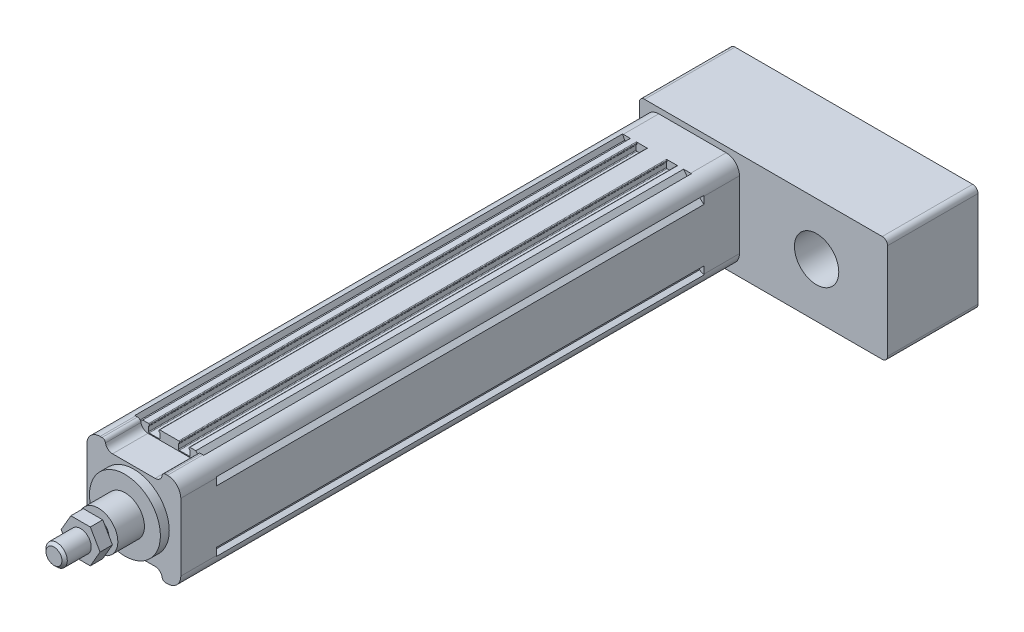
SolidWorks part; units mm, degrees
ref_plane "Front" through (0, 0, 0) normal (0, 0, 1) x (1, 0, 0)
ref_plane "Top" through (0, 0, 0) normal (0, 1, 0) x (1, 0, 0)
ref_plane "Right" through (0, 0, 0) normal (1, 0, 0) x (0, 0, -1)
sketch "草图1" plane through (0, 0, 0) normal (0, 0, 1) x (1, 0, 0)
  line L0 (19.7737, 3) -> (23.3, 3)
  line L1 (23.3, 3) -> (23.3, -3)
  line L2 (23.3, -3) -> (19.7737, -3)
  line L3 (-19.7737, -3) -> (-23.3, -3)
  line L4 (-23.3, -3) -> (-23.3, 3)
  line L5 (-23.3, 3) -> (-19.7737, 3)
  line L6 (-18.2, 24) -> (-19.4434, 26.4869)
  line L7 (-26.4869, 19.4434) -> (-24, 18.2)
  line L8 (-24, 18.2) -> (-24, 17.1)
  line L9 (-24, 17.1) -> (-26.5, 15)
  line L10 (-26.5, 15) -> (-26.5, -15)
  line L11 (-26.5, -15) -> (-24, -17.1)
  line L12 (-24, -17.1) -> (-24, -18.2)
  line L13 (-24, -18.2) -> (-26.4869, -19.4434)
  line L14 (-19.4434, -26.4869) -> (-18.2, -24)
  line L15 (-18.2, -24) -> (-17.1, -24)
  line L16 (-17.1, -24) -> (-15, -26.5)
  line L17 (-15, -26.5) -> (-11.65, -26.5)
  line L18 (-11.25, -26.1) -> (-11.25, -25.6)
  line L19 (-11.65, -25.2) -> (-11.75, -25.2)
  line L20 (-11.75, -25.2) -> (-11.75, -22.4)
  line L21 (-11.35, -22) -> (-5.65, -22)
  line L22 (-5.25, -22.4) -> (-5.25, -25.2)
  line L23 (-5.25, -25.2) -> (-5.35, -25.2)
  line L24 (-5.75, -25.6) -> (-5.75, -26.1)
  line L25 (-5.35, -26.5) -> (5.35, -26.5)
  line L26 (5.75, -26.1) -> (5.75, -25.6)
  line L27 (5.35, -25.2) -> (5.25, -25.2)
  line L28 (5.25, -25.2) -> (5.25, -22.4)
  line L29 (5.65, -22) -> (11.35, -22)
  line L30 (11.75, -22.4) -> (11.75, -25.2)
  line L31 (11.75, -25.2) -> (11.65, -25.2)
  line L32 (11.25, -25.6) -> (11.25, -26.1)
  line L33 (11.65, -26.5) -> (15, -26.5)
  line L34 (15, -26.5) -> (17.1, -24)
  line L35 (17.1, -24) -> (18.2, -24)
  line L36 (18.2, -24) -> (19.4434, -26.4869)
  line L37 (26.4869, -19.4434) -> (24, -18.2)
  line L38 (24, -18.2) -> (24, -17.1)
  line L39 (24, -17.1) -> (26.5, -15)
  line L40 (26.5, -15) -> (26.5, 15)
  line L41 (26.5, 15) -> (24, 17.1)
  line L42 (24, 17.1) -> (24, 18.2)
  line L43 (24, 18.2) -> (26.4869, 19.4434)
  line L44 (19.4434, 26.4869) -> (18.2, 24)
  line L45 (18.2, 24) -> (17.1, 24)
  line L46 (17.1, 24) -> (15, 26.5)
  line L47 (15, 26.5) -> (11.65, 26.5)
  line L48 (11.25, 26.1) -> (11.25, 25.6)
  line L49 (11.65, 25.2) -> (11.75, 25.2)
  line L50 (11.75, 25.2) -> (11.75, 22.4)
  line L51 (11.35, 22) -> (5.65, 22)
  line L52 (5.25, 22.4) -> (5.25, 25.2)
  line L53 (5.25, 25.2) -> (5.35, 25.2)
  line L54 (5.75, 25.6) -> (5.75, 26.1)
  line L55 (5.35, 26.5) -> (-5.35, 26.5)
  line L56 (-5.75, 26.1) -> (-5.75, 25.6)
  line L57 (-5.35, 25.2) -> (-5.25, 25.2)
  line L58 (-5.25, 25.2) -> (-5.25, 22.4)
  line L59 (-5.65, 22) -> (-11.35, 22)
  line L60 (-11.75, 22.4) -> (-11.75, 25.2)
  line L61 (-11.75, 25.2) -> (-11.65, 25.2)
  line L62 (-11.25, 25.6) -> (-11.25, 26.1)
  line L63 (-11.65, 26.5) -> (-15, 26.5)
  line L64 (-15, 26.5) -> (-17.1, 24)
  line L65 (-17.1, 24) -> (-18.2, 24)
  arc A0 (19.7737, 3) -> (-19.7737, 3) centre (0, 0) ccw
  arc A1 (-19.7737, -3) -> (19.7737, -3) centre (0, 0) ccw
  circle A2 centre (19, 19) radius 2.1
  circle A3 centre (19, -19) radius 2.1
  circle A4 centre (-19, -19) radius 2.1
  circle A5 centre (-19, 19) radius 2.1
  arc A6 (-19.4434, 26.4869) -> (-26.4869, 19.4434) centre (-19, 19) ccw
  arc A7 (-26.4869, -19.4434) -> (-19.4434, -26.4869) centre (-19, -19) ccw
  arc A8 (-11.65, -26.5) -> (-11.25, -26.1) centre (-11.65, -26.1) ccw
  arc A9 (-11.25, -25.6) -> (-11.65, -25.2) centre (-11.65, -25.6) ccw
  arc A10 (-11.35, -22) -> (-11.75, -22.4) centre (-11.35, -22.4) ccw
  arc A11 (-5.25, -22.4) -> (-5.65, -22) centre (-5.65, -22.4) ccw
  arc A12 (-5.35, -25.2) -> (-5.75, -25.6) centre (-5.35, -25.6) ccw
  arc A13 (-5.75, -26.1) -> (-5.35, -26.5) centre (-5.35, -26.1) ccw
  arc A14 (5.35, -26.5) -> (5.75, -26.1) centre (5.35, -26.1) ccw
  arc A15 (5.75, -25.6) -> (5.35, -25.2) centre (5.35, -25.6) ccw
  arc A16 (5.65, -22) -> (5.25, -22.4) centre (5.65, -22.4) ccw
  arc A17 (11.75, -22.4) -> (11.35, -22) centre (11.35, -22.4) ccw
  arc A18 (11.65, -25.2) -> (11.25, -25.6) centre (11.65, -25.6) ccw
  arc A19 (11.25, -26.1) -> (11.65, -26.5) centre (11.65, -26.1) ccw
  arc A20 (19.4434, -26.4869) -> (26.4869, -19.4434) centre (19, -19) ccw
  arc A21 (26.4869, 19.4434) -> (19.4434, 26.4869) centre (19, 19) ccw
  arc A22 (11.65, 26.5) -> (11.25, 26.1) centre (11.65, 26.1) ccw
  arc A23 (11.25, 25.6) -> (11.65, 25.2) centre (11.65, 25.6) ccw
  arc A24 (11.35, 22) -> (11.75, 22.4) centre (11.35, 22.4) ccw
  arc A25 (5.25, 22.4) -> (5.65, 22) centre (5.65, 22.4) ccw
  arc A26 (5.35, 25.2) -> (5.75, 25.6) centre (5.35, 25.6) ccw
  arc A27 (5.75, 26.1) -> (5.35, 26.5) centre (5.35, 26.1) ccw
  arc A28 (-5.35, 26.5) -> (-5.75, 26.1) centre (-5.35, 26.1) ccw
  arc A29 (-5.75, 25.6) -> (-5.35, 25.2) centre (-5.35, 25.6) ccw
  arc A30 (-5.65, 22) -> (-5.25, 22.4) centre (-5.65, 22.4) ccw
  arc A31 (-11.75, 22.4) -> (-11.35, 22) centre (-11.35, 22.4) ccw
  arc A32 (-11.65, 25.2) -> (-11.25, 25.6) centre (-11.65, 25.6) ccw
  arc A33 (-11.25, 26.1) -> (-11.65, 26.5) centre (-11.65, 26.1) ccw
extrude "凸台-拉伸1" add sketch "草图1" along normal blind 275
sketch "草图6" plane through (0, 0, 275) normal (0, 0, 1) x (1, 0, 0)
  line L0 (0, 0) -> (19, 0) construction
  line L2 (-26.5, -19) -> (-26.5, 19)
  line L3 (-19, 26.5) -> (-17.9161, 26.5)
  line L4 (26.5, -19) -> (26.5, 19)
  line L5 (-26.5, -26.5) -> (26.5, 26.5) construction
  line L6 (-26.5, 26.5) -> (26.5, -26.5) construction
  line L7 (-12, 21.5) -> (12, 21.5)
  line L9 (19, 26.5) -> (17.9161, 26.5)
  line L10 (19, -26.5) -> (17.9161, -26.5)
  line L11 (-12, -21.5) -> (12, -21.5)
  line L12 (-19, -26.5) -> (-17.9161, -26.5)
  arc A0 (12, 21.5) -> (15.9441, 24.8333) centre (12, 25.5) ccw
  arc A1 (-15.9441, 24.8333) -> (-12, 21.5) centre (-12, 25.5) ccw
  arc A2 (-15.9441, 24.8333) -> (-17.9161, 26.5) centre (-17.9161, 24.5) ccw
  arc A3 (15.9441, 24.8333) -> (17.9161, 26.5) centre (17.9161, 24.5) cw
  arc A4 (-26.5, -19) -> (-19, -26.5) centre (-19, -19) ccw
  arc A5 (19, -26.5) -> (26.5, -19) centre (19, -19) ccw
  arc A6 (26.5, 19) -> (19, 26.5) centre (19, 19) ccw
  arc A7 (-26.5, 19) -> (-19, 26.5) centre (-19, 19) cw
  arc A8 (15.9441, -24.8333) -> (17.9161, -26.5) centre (17.9161, -24.5) ccw
  arc A9 (12, -21.5) -> (15.9441, -24.8333) centre (12, -25.5) cw
  arc A10 (-15.9441, -24.8333) -> (-12, -21.5) centre (-12, -25.5) cw
  arc A11 (-15.9441, -24.8333) -> (-17.9161, -26.5) centre (-17.9161, -24.5) cw
  point P0 (0, 0)
  point P9 (0, 21.5)
  point P13 (20, 20.8461)
  point P16 (-12, 20.8461)
  dimension "D5" = 4
  dimension "D6" = 2
  dimension "D7" = 2
  dimension "D9" = 7.5
  dimension "D1" = 53
  dimension "D2" = 53
  dimension "D3" = 26.5
  dimension "D4" = 24
  dimension "D8" = 5
extrude "凸台-拉伸2" add sketch "草图6" along normal blind 20
sketch "草图7" plane through (0, 0, 295) normal (0, 0, 1) x (1, 0, 0)
  circle A0 centre (0, 0) radius 20
  dimension "D1" = 40
extrude "凸台-拉伸3" add sketch "草图7" along normal blind 5
sketch "草图9" plane through (0, 0, 300) normal (0, 0, 1) x (1, 0, 0)
  circle A0 centre (0, 0) radius 11
  dimension "D1" = 22
extrude "凸台-拉伸4" add sketch "草图9" along normal blind 15
sketch "草图10" plane through (0, 0, 315) normal (0, 0, 1) x (1, 0, 0)
  circle A0 centre (0, 0) radius 6
  dimension "D1" = 12
extrude "凸台-拉伸5" add sketch "草图10" along normal blind 25
sketch "草图11" plane through (0, 0, 0) normal (0, 0, -1) x (-1, 0, 0)
  line L1 (-19, -26.5) -> (19, -26.5)
  line L2 (-26.5, -19) -> (-26.5, 19)
  line L3 (-19, 26.5) -> (19, 26.5)
  line L4 (26.5, -19) -> (26.5, 19)
  line L5 (-26.5, -26.5) -> (26.5, 26.5) construction
  line L6 (-26.5, 26.5) -> (26.5, -26.5) construction
  arc A0 (-26.5, -19) -> (-19, -26.5) centre (-19, -19) ccw
  arc A1 (19, -26.5) -> (26.5, -19) centre (19, -19) ccw
  arc A2 (26.5, 19) -> (19, 26.5) centre (19, 19) ccw
  arc A3 (-26.5, 19) -> (-19, 26.5) centre (-19, 19) cw
  point P0 (0, 0)
  dimension "D3" = 7.5
  dimension "D1" = 53
  dimension "D2" = 53
extrude "凸台-拉伸6" add sketch "草图11" along normal blind 20
sketch "草图12" plane through (0, 0, -20) normal (0, 0, -1) x (-1, 0, 0)
  line L1 (-107, -30.4042) -> (27, -30.4042)
  line L2 (-110, -27.4042) -> (-110, 26.5958)
  line L3 (-107, 29.5958) -> (27, 29.5958)
  line L4 (30, -27.4042) -> (30, 26.5958)
  line L5 (-110, -30.4042) -> (30, 29.5958) construction
  line L6 (-110, 29.5958) -> (30, -30.4042) construction
  arc A0 (27, 29.5958) -> (30, 26.5958) centre (27, 26.5958) cw
  arc A1 (30, -27.4042) -> (27, -30.4042) centre (27, -27.4042) cw
  arc A2 (-110, -27.4042) -> (-107, -30.4042) centre (-107, -27.4042) ccw
  arc A3 (-110, 26.5958) -> (-107, 29.5958) centre (-107, 26.5958) cw
  point P0 (-40, -0.4042)
  dimension "D4" = 3
  dimension "D1" = 60
  dimension "D2" = 140
  dimension "D3" = 30
extrude "凸台-拉伸7" add sketch "草图12" along normal blind 51
sketch "草图13" plane through (0, 0, -20) normal (0, 0, 1) x (1, 0, 0)
  circle A0 centre (70, 0) radius 12.5
  dimension "D2" = 25
  dimension "D1" = 70
extrude "切除-拉伸2" cut sketch "草图13" against normal blind 30
hole_wizard "M6 螺纹孔1" positions "草图14" profile "草图15" tap size "M6" standard "GB"
sketch "草图14" plane through (0, 0, -71) normal (0, 0, -1) x (-1, 0, 0)
  line L0 (30, -27.4042) -> (30, 26.5958) construction
  point P0 (19, -19)
  dimension "D1" = 11
  dimension "D2" = 19
sketch "草图15" plane through (-19, -19, -71) normal (1, 0, 0) x (0, 1, 0)
  line L0 (0, 0) -> (0, 16.5022)
  line L1 (0, 16.5022) -> (2.5, 15)
  line L2 (2.5, 15) -> (2.5, 0)
  line L5 (2.5, 0) -> (0, 0)
  line L10 (0, 16.5022) -> (-2.5, 15) construction
  line L11 (0, -6.35) -> (0, 107.95) construction
  dimension "螺纹孔钻头直径" = 5
  dimension "螺纹孔钻头深度" = 15
  dimension "导头角度" = 118
cosmetic thread "孔螺蚊线4" parameters "D1"=12, "D2"=6
pattern_linear "阵列(线性)1" count 2 spacing 38 along (0, 1, 0) count 2 spacing 38 along (1, 0, 0) of "M6 螺纹孔1"
hole_wizard "M6 螺纹孔2" positions "草图16" profile "草图17" tap size "M6" standard "GB"
sketch "草图16" plane through (0, 0, -71) normal (0, 0, -1) x (-1, 0, 0)
  circle A1 centre (-19, 19) radius 2.5 construction
  circle A2 centre (-19, -19) radius 2.5 construction
  point P0 (-84, -19)
  point P2 (-84, 19)
  dimension "D3" = 65
  dimension "D1" = 19
  dimension "D2" = 19
  dimension "D4" = 65
sketch "草图17" plane through (84, -19, -71) normal (1, 0, 0) x (0, 1, 0)
  line L0 (0, 0) -> (0, 16.5022)
  line L1 (0, 16.5022) -> (2.5, 15)
  line L2 (2.5, 15) -> (2.5, 0)
  line L5 (2.5, 0) -> (0, 0)
  line L10 (0, 16.5022) -> (-2.5, 15) construction
  line L11 (0, -6.35) -> (0, 107.95) construction
  dimension "螺纹孔钻头直径" = 5
  dimension "螺纹孔钻头深度" = 15
  dimension "导头角度" = 118
cosmetic thread "孔螺蚊线5" parameters "D1"=12, "D2"=6
cosmetic thread "孔螺蚊线6" parameters "D1"=12, "D2"=6
hole_wizard "M6 螺纹孔3" positions "草图19" profile "草图20" tap size "M6" standard "GB"
sketch "草图19" plane through (-26.5, 0, 0) normal (-1, 0, 0) x (0, 0, 1)
  line L0 (295, 19) -> (295, -19) construction
  point P0 (285, 11)
  point P2 (285, -11)
  dimension "D1" = 10
  dimension "D2" = 10
  dimension "D3" = 22
  dimension "D4" = 11
sketch "草图20" plane through (-26.5, 11, 285) normal (0, 1, 0) x (0, 0, 1)
  line L0 (0, 0) -> (0, 16.5022)
  line L1 (0, 16.5022) -> (2.5, 15)
  line L2 (2.5, 15) -> (2.5, 0)
  line L5 (2.5, 0) -> (0, 0)
  line L10 (0, 16.5022) -> (-2.5, 15) construction
  line L11 (0, -6.35) -> (0, 107.95) construction
  dimension "螺纹孔钻头直径" = 5
  dimension "螺纹孔钻头深度" = 15
  dimension "导头角度" = 118
cosmetic thread "孔螺蚊线7" parameters "D1"=12, "D2"=6
cosmetic thread "孔螺蚊线8" parameters "D1"=12, "D2"=6
hole_wizard "M6 螺纹孔4" positions "草图21" profile "草图22" tap size "M6" standard "GB"
sketch "草图21" plane through (-26.5, 0, 0) normal (-1, 0, 0) x (0, 0, 1)
  line L0 (-20, -27.4042) -> (-20, 26.5958) construction
  line L1 (-20, -19) -> (-20, 19) construction
  point P0 (-10, 11)
  point P2 (-10, -11)
  dimension "D1" = 10
  dimension "D2" = 10
  dimension "D3" = 11
  dimension "D4" = 11
sketch "草图22" plane through (-26.5, 11, -10) normal (0, 1, 0) x (0, 0, 1)
  line L0 (0, 0) -> (0, 16.5022)
  line L1 (0, 16.5022) -> (2.5, 15)
  line L2 (2.5, 15) -> (2.5, 0)
  line L5 (2.5, 0) -> (0, 0)
  line L10 (0, 16.5022) -> (-2.5, 15) construction
  line L11 (0, -6.35) -> (0, 107.95) construction
  dimension "螺纹孔钻头直径" = 5
  dimension "螺纹孔钻头深度" = 15
  dimension "导头角度" = 118
cosmetic thread "孔螺蚊线9" parameters "D1"=12, "D2"=6
cosmetic thread "孔螺蚊线10" parameters "D1"=12, "D2"=6
chamfer "倒角1" distance 1.5 angle 45 1 edges at (6, 0, 340)
sketch "草图23" plane through (0, 0, 315) normal (0, 0, 1) x (1, 0, 0)
  line L1 (10.9697, 0) -> (5.4848, 9.5)
  line L2 (5.4848, 9.5) -> (-5.4848, 9.5)
  line L3 (-5.4848, 9.5) -> (-10.9697, 0)
  line L4 (-10.9697, 0) -> (-5.4848, -9.5)
  line L5 (-5.4848, -9.5) -> (5.4848, -9.5)
  line L6 (5.4848, -9.5) -> (10.9697, 0)
  circle A0 centre (0, 0) radius 9.5 construction
  dimension "D1" = 19
extrude "凸台-拉伸8" add sketch "草图23" along normal blind 7 from offset 3
